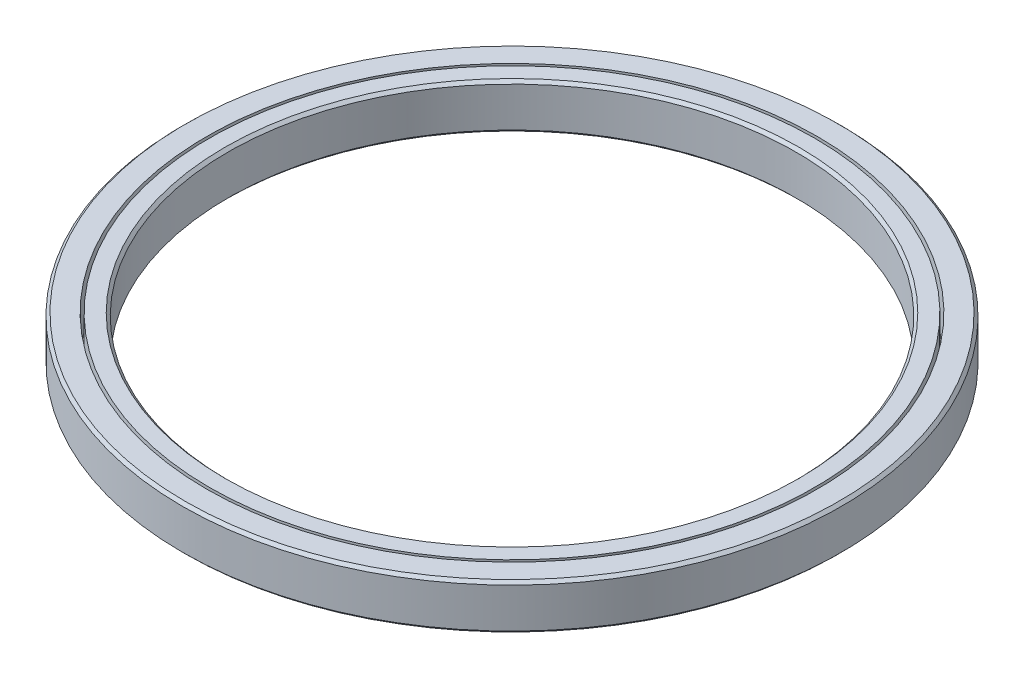
SolidWorks part; units mm, degrees
ref_plane "前视基准面" through (0, 0, 0) normal (0, 0, 1) x (1, 0, 0)
ref_plane "上视基准面" through (0, 0, 0) normal (0, 1, 0) x (1, 0, 0)
ref_plane "右视基准面" through (0, 0, 0) normal (1, 0, 0) x (0, 0, -1)
sketch "草图1" plane through (0, 0, 0) normal (0, 1, 0) x (1, 0, 0)
  circle A0 centre (0, 0) radius 58
  circle A1 centre (0, 0) radius 53.75
  dimension "D1" = 116
  dimension "D2" = 107.5
extrude "凸台-拉伸1" add sketch "草图1" along normal blind 8
sketch "草图2" plane through (0, 0, 0) normal (0, 1, 0) x (1, 0, 0)
  circle A0 centre (0, 0) radius 53.25
  circle A1 centre (0, 0) radius 50
  dimension "D1" = 106.5
  dimension "D2" = 100
extrude "凸台-拉伸2" add sketch "草图2" along normal blind 8
sketch "草图4" plane through (0, 8, 0) normal (0, 1, 0) x (1, 0, 0)
  circle A1 centre (0, 0) radius 58
  circle A2 centre (0, 0) radius 56
  dimension "D2" = 112
extrude "切除-拉伸3" [suppressed] cut sketch "草图4" against normal blind 2
sketch "草图5" plane through (0, 8, 0) normal (0, 1, 0) x (1, 0, 0)
  circle A0 centre (0, 0) radius 52
  dimension "D1" = 104
extrude "切除-拉伸4" [suppressed] cut sketch "草图5" against normal blind 1
ref_plane "基准面1" [suppressed] through (0, 4, 0) normal (0, 1, 0) x (1, 0, 0)
sketch "草图6" plane through (0, 0, 0) normal (0, -1, 0) x (1, 0, 0)
  circle A0 centre (0, 0) radius 52
  dimension "D1" = 104
extrude "切除-拉伸5" [suppressed] cut sketch "草图6" against normal blind 2
sketch "草图7" plane through (0, 0, 0) normal (0, -1, 0) x (1, 0, 0)
  circle A1 centre (0, 0) radius 58
  circle A2 centre (0, 0) radius 56
  dimension "D1" = 112
extrude "切除-拉伸6" [suppressed] cut sketch "草图7" against normal blind 2
chamfer "倒角1" distance 0.5 angle 45 2 edges at (0, 0, 58) (0, 8, 58)
chamfer "倒角2" distance 0.5 angle 45 2 edges at (0, 0, 50) (0, 8, 50)
